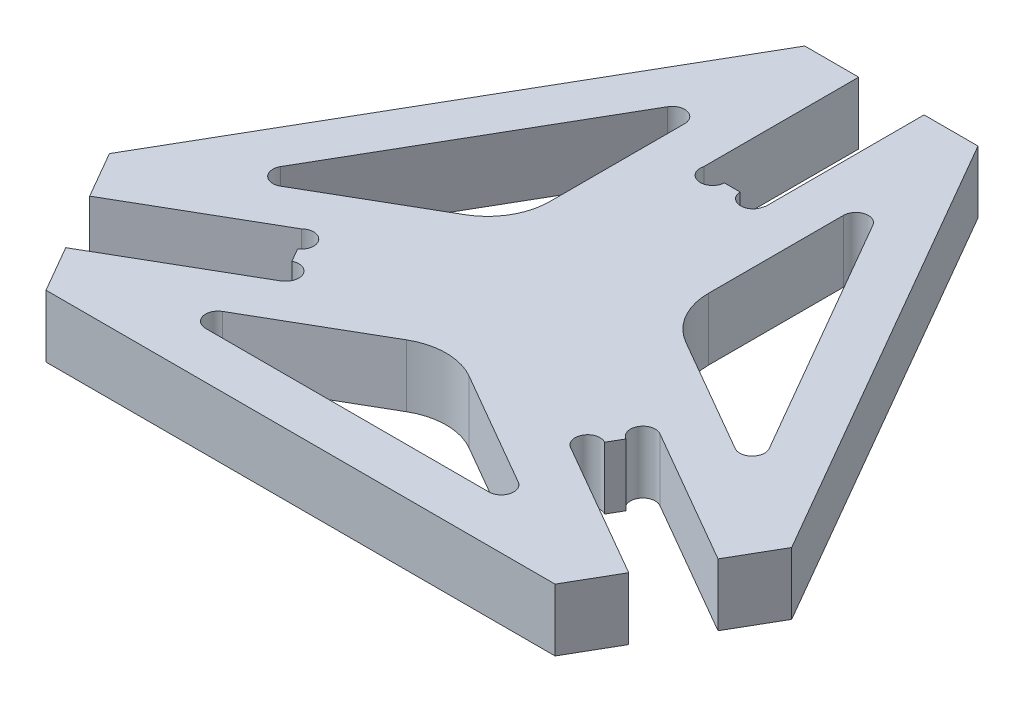
SolidWorks part; units mm, degrees
material "自定义塑料碳纤维-1.6"
ref_plane "前视基准面" through (0, 0, 0) normal (0, 0, 1) x (1, 0, 0)
ref_plane "上视基准面" through (0, 0, 0) normal (0, 1, 0) x (1, 0, 0)
ref_plane "右视基准面" through (0, 0, 0) normal (1, 0, 0) x (0, 0, -1)
other "Configuration Table"
sketch "草图1" plane through (0, 0, 0) normal (0, 1, 0) x (1, 0, 0)
  line L0 (0, 0) -> (-11.1417, -19.298)
  line L1 (-11.1417, -19.298) -> (11.1417, -19.298)
  line L2 (11.1417, -19.298) -> (0, 0)
  line L3 (1.05, -1.8187) -> (-1.05, -1.8187)
  line L4 (10.0917, -17.4794) -> (9.0417, -19.298)
  line L5 (-10.0917, -17.4794) -> (-9.0417, -19.298)
  line L6 (1.05, -1.8187) -> (2.7821, -1.8187)
  line L7 (2.7821, -1.8187) -> (10.9578, -15.9794)
  line L8 (10.9578, -15.9794) -> (10.0917, -17.4794)
  line L9 (9.0417, -19.298) -> (8.1757, -20.798)
  line L10 (8.1757, -20.798) -> (-8.1757, -20.798)
  line L11 (-8.1757, -20.798) -> (-9.0417, -19.298)
  line L12 (-1.05, -1.8187) -> (-2.7821, -1.8187)
  line L13 (-2.7821, -1.8187) -> (-10.9578, -15.9794)
  line L14 (-10.9578, -15.9794) -> (-10.0917, -17.4794)
  line L15 (1.05, -1.8187) -> (1.05, -6.9187)
  line L16 (1.05, -6.9187) -> (-1.05, -6.9187)
  line L17 (-1.05, -6.9187) -> (-1.05, -1.8187)
  line L18 (10.0917, -17.4794) -> (5.675, -14.9294)
  line L19 (5.675, -14.9294) -> (4.625, -16.748)
  line L20 (4.625, -16.748) -> (9.0417, -19.298)
  line L21 (-10.0917, -17.4794) -> (-5.675, -14.9294)
  line L22 (-5.675, -14.9294) -> (-4.625, -16.748)
  line L23 (-4.625, -16.748) -> (-9.0417, -19.298)
  dimension "D1" = 60
  dimension "D2" = 60
  dimension "D3" = 9.25
  dimension "D4" = 2.1
  dimension "D5" = 2.1
  dimension "D6" = 2.1
  dimension "D7" = 60
  dimension "D8" = 60
  dimension "D9" = 1.5
  dimension "D10" = 1.5
  dimension "D11" = 1.5
  dimension "D12" = 5.1
  dimension "D13" = 5.1
  dimension "D14" = 5.1
extrude "凸台-拉伸1" add sketch "草图1" along normal mid plane 2 contours L11 L10 L9 L1 | L8 L7 L6 L2 | L13 L14 L0 L12 | L22 L23 L1 L20 L19 L18 L2 L15 L16 L17 L0 L21
sketch "草图2" plane through (0, 1, 0) normal (0, 1, 0) x (1, 0, 0)
  line L0 (5.675, -14.9294) -> (-6.3449, -7.9897)
  line L1 (-5.675, -14.9294) -> (6.3449, -7.9897)
  line L2 (1.05, -6.9187) -> (1.05, -12.2591)
  line L3 (2.55, -6.9187) -> (2.55, -12.2591)
  line L4 (6.425, -13.6304) -> (-5.5949, -6.6907)
  line L5 (2.55, -6.9187) -> (2.55, -4.4167)
  line L6 (2.55, -4.4167) -> (8.5917, -14.8813)
  line L7 (8.5917, -14.8813) -> (6.425, -13.6304)
  line L8 (5.15, -15.8387) -> (-1.05, -12.2591)
  line L9 (-5.15, -15.8387) -> (0, -12.8654)
  line L10 (6.0417, -19.298) -> (-6.0417, -19.298)
  line L11 (3.875, -18.0471) -> (6.0417, -19.298)
  line L12 (3.875, -18.0471) -> (-0.75, -15.3768)
  line L13 (-3.875, -18.0471) -> (8.1449, -11.1074)
  line L14 (-6.0417, -19.298) -> (-3.875, -18.0471)
  line L15 (-8.5917, -14.8813) -> (-2.55, -4.4167)
  line L16 (-6.425, -13.6304) -> (-8.5917, -14.8813)
  line L17 (-6.425, -13.6304) -> (-1.8, -10.9601)
  line L18 (-9.0417, -19.298) -> (-8.1757, -20.798)
  line L19 (-8.1757, -20.798) -> (8.1757, -20.798)
  line L20 (8.1757, -20.798) -> (9.0417, -19.298)
  line L21 (9.0417, -19.298) -> (4.625, -16.748)
  line L22 (4.625, -16.748) -> (5.675, -14.9294)
  line L23 (5.675, -14.9294) -> (10.0917, -17.4794)
  line L24 (10.0917, -17.4794) -> (10.9578, -15.9794)
  line L25 (10.9578, -15.9794) -> (2.7821, -1.8187)
  line L26 (2.7821, -1.8187) -> (1.05, -1.8187)
  line L27 (1.05, -1.8187) -> (1.05, -6.9187)
  line L28 (1.05, -6.9187) -> (-1.05, -6.9187)
  line L29 (-1.05, -6.9187) -> (-1.05, -1.8187)
  line L30 (-1.05, -1.8187) -> (-2.7821, -1.8187)
  line L31 (-2.7821, -1.8187) -> (-10.9578, -15.9794)
  line L32 (-10.9578, -15.9794) -> (-10.0917, -17.4794)
  line L33 (-10.0917, -17.4794) -> (-5.675, -14.9294)
  line L34 (-5.675, -14.9294) -> (-4.625, -16.748)
  line L35 (-4.625, -16.748) -> (-9.0417, -19.298)
  line L36 (-9.0417, -19.298) -> (-8.1757, -20.798)
  line L37 (-8.1757, -20.798) -> (8.1757, -20.798)
  line L38 (8.1757, -20.798) -> (9.0417, -19.298)
  line L39 (9.0417, -19.298) -> (4.625, -16.748)
  line L40 (4.625, -16.748) -> (5.675, -14.9294)
  line L41 (5.675, -14.9294) -> (10.0917, -17.4794)
  line L42 (10.0917, -17.4794) -> (10.9578, -15.9794)
  line L43 (10.9578, -15.9794) -> (2.7821, -1.8187)
  line L44 (2.7821, -1.8187) -> (1.05, -1.8187)
  line L45 (1.05, -1.8187) -> (1.05, -6.9187)
  line L46 (1.05, -6.9187) -> (-1.05, -6.9187)
  line L47 (-1.05, -6.9187) -> (-1.05, -1.8187)
  line L48 (-1.05, -1.8187) -> (-2.7821, -1.8187)
  line L49 (-2.7821, -1.8187) -> (-10.9578, -15.9794)
  line L50 (-10.9578, -15.9794) -> (-10.0917, -17.4794)
  line L51 (-10.0917, -17.4794) -> (-5.675, -14.9294)
  line L52 (-5.675, -14.9294) -> (-4.625, -16.748)
  line L53 (-4.625, -16.748) -> (-9.0417, -19.298)
  line L54 (-2.55, -6.9187) -> (-2.55, -20.798)
  line L55 (-2.55, -4.4167) -> (-2.55, -6.9187)
  point P46 (0, -12.8654)
  dimension "D4" = 1.5
  dimension "D1" = 0
  dimension "D2" = 1.5
  dimension "D3" = 1.5
  dimension "D5" = 3
extrude "切除-拉伸1" cut sketch "草图2" against normal mid plane 10
sketch "草图4" plane through (0, 1, 0) normal (0, 1, 0) x (1, 0, 0)
  line L0 (4.625, -16.748) -> (5.675, -14.9294) construction
  circle A0 centre (5.475, -15.2758) radius 0.4
  circle A1 centre (4.825, -16.4016) radius 0.4
  dimension "D1" = 0.8
  dimension "D2" = 0.8
extrude "切除-拉伸2" cut sketch "草图4" against normal mid plane 10
pattern_circular "阵列(圆周)3" count 3 every 120 about axis through (-0.0132, 0, 12.8578) along (0, 1, 0) of "切除-拉伸2"
fillet "圆角1" radius 0.4 6 edges at (-8.5917, 0, 14.8813) (2.55, 0, 4.4167) (8.5917, 0, 14.8813) (6.0417, 0, 19.298) (-6.0417, 0, 19.298) (-2.55, 0, 4.4167)
fillet "圆角2" radius 2 3 edges at (2.55, 0, 11.3931) (0, 0, 15.8098) (-2.55, 0, 11.3931)
